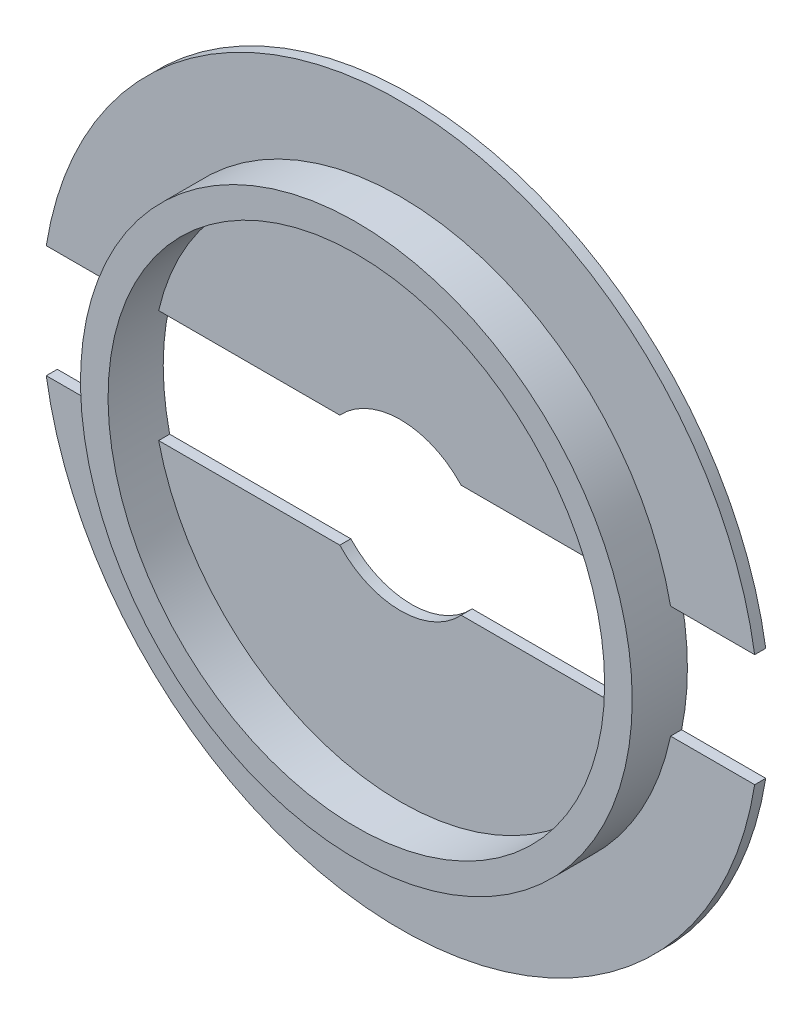
SolidWorks part; units mm, degrees
ref_plane "Plano frontal" through (0, 0, 0) normal (0, 0, 1) x (1, 0, 0)
ref_plane "Plano superior" through (0, 0, 0) normal (0, 1, 0) x (1, 0, 0)
ref_plane "Plano direito" through (0, 0, 0) normal (1, 0, 0) x (0, 0, -1)
sketch "Esboço1" plane through (0, 0, 0) normal (0, 0, 1) x (1, 0, 0)
  line L3 (-64.8709, 4.0952) -> (-65, 4.0952)
  line L4 (-10.9982, 10.2) -> (-64.1947, 10.2)
  line L5 (10.9982, 10.2) -> (64.1947, 10.2)
  line L6 (-10.9982, -10.2) -> (-64.1947, -10.2)
  line L7 (10.9982, -10.2) -> (64.1947, -10.2)
  circle A0 centre (0, 0) radius 65
  arc A1 (-10.9982, -10.2) -> (10.9982, -10.2) centre (0, 0) ccw
  arc A2 (10.9982, 10.2) -> (-10.9982, 10.2) centre (0, 0) ccw
  dimension "D1" = 130
  dimension "D2" = 30
extrude "Ressalto-extrusão1" add sketch "Esboço1" along normal blind 2 contours A2 L5 A0 L4 | A1 L6 A0 L7
sketch "Esboço2" plane through (0, 0, 0) normal (0, 0, 1) x (1, 0, 0)
  circle A0 centre (0, 0) radius 45
  circle A1 centre (0, 0) radius 50
  dimension "D1" = 90
  dimension "D2" = 100
extrude "Ressalto-extrusão2" add sketch "Esboço2" along normal blind 10
